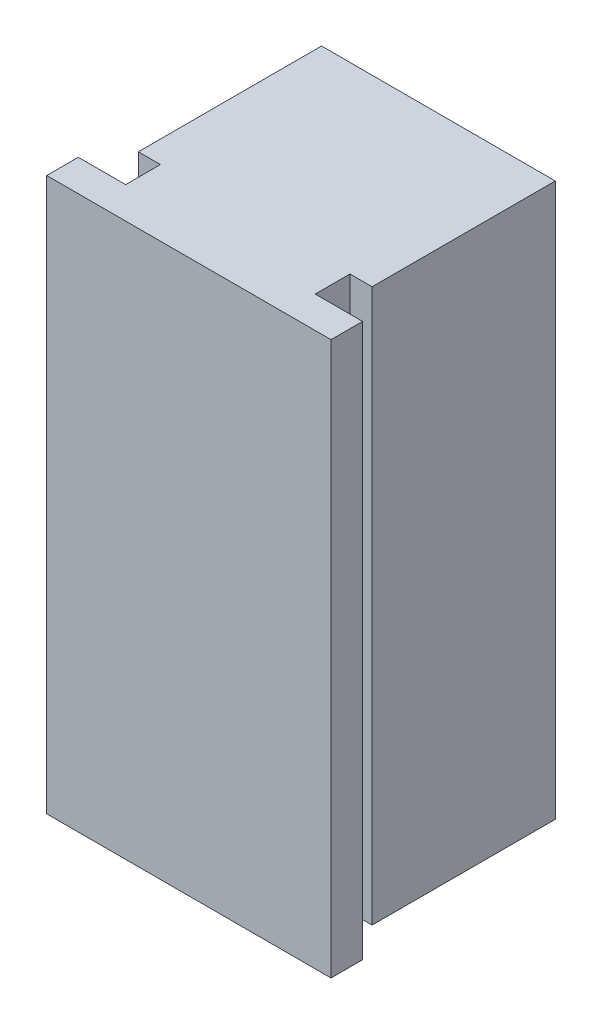
SolidWorks part; units mm, degrees
ref_plane "Front Plane" through (0, 0, 0) normal (0, 0, 1) x (1, 0, 0)
ref_plane "Top Plane" through (0, 0, 0) normal (0, 1, 0) x (1, 0, 0)
ref_plane "Right Plane" through (0, 0, 0) normal (1, 0, 0) x (0, 0, -1)
sketch "Sketch1" plane through (0, 0, 0) normal (0, 1, 0) x (1, 0, 0)
  line L0 (8.9355, 6.1935) -> (8.9355, -22) construction
  line L1 (1.5355, -14.9613) -> (1.5355, -3.3613)
  line L2 (-0.0645, -19.1613) -> (17.9355, -19.1613)
  line L3 (8.9355, -19.1613) -> (8.9355, -17.1613)
  line L4 (-0.0645, -17.1613) -> (17.9355, -17.1613)
  line L5 (17.9355, -19.1613) -> (17.9355, -17.1613)
  line L6 (2.9355, -17.1613) -> (14.9355, -17.1613)
  line L7 (8.9355, -17.1613) -> (8.9355, -14.9613)
  line L8 (2.9355, -14.9613) -> (14.9355, -14.9613)
  line L9 (14.9355, -17.1613) -> (14.9355, -14.9613)
  line L10 (1.5355, -14.9613) -> (16.3355, -14.9613)
  line L11 (8.9355, -14.9613) -> (8.9355, -3.3613)
  line L12 (1.5355, -3.3613) -> (16.3355, -3.3613)
  line L13 (16.3355, -14.9613) -> (16.3355, -3.3613)
  line L14 (2.9355, -17.1613) -> (2.9355, -14.9613)
  line L15 (-0.0645, -19.1613) -> (-0.0645, -17.1613)
  dimension "D1" = 2
  dimension "D2" = 2.2
  dimension "D3" = 15.8
  dimension "D4" = 9
  dimension "D5" = 6
  dimension "D6" = 7.4
extrude "Boss-Extrude1" add sketch "Sketch1" along normal blind 35 contours L12 L1 L10 L8 L11 | L10 L13 L12 L11 L8 | L4 L9 L8 L7 | L14 L4 L7 L8 | L15 L2 L3 L4 | L2 L5 L4 L3
sketch "Sketch2" plane through (0, 0, 3.3613) normal (0, 0, -1) x (-1, 0, 0)
  line L0 (-8.9355, 35) -> (-8.9355, 0) construction
  line L1 (-1.5355, 35) -> (-16.3355, 35) construction
  line L2 (-1.5355, 0) -> (-16.3355, 0) construction
  circle A0 centre (-8.9355, 17.5) radius 4.5
extrude "Cut-Extrude1" cut sketch "Sketch2" against normal blind 12
